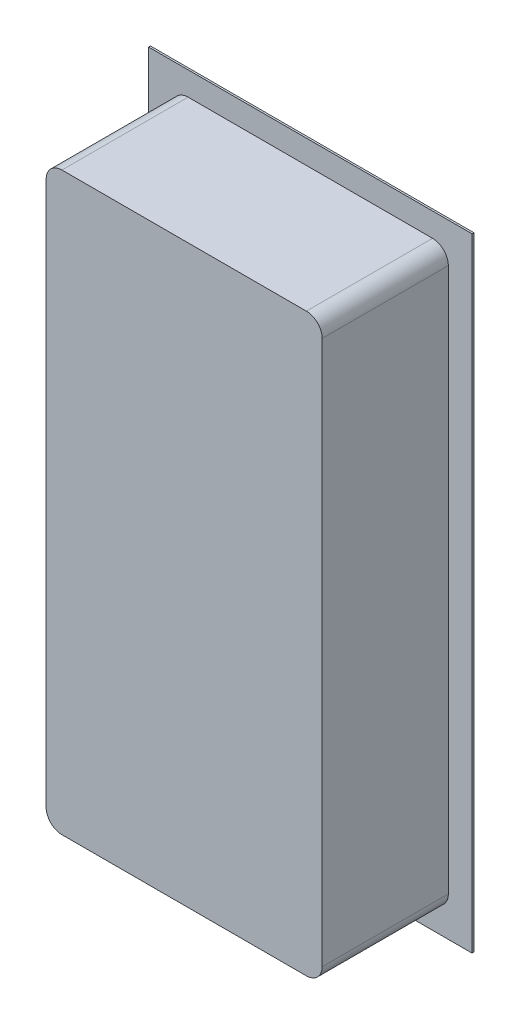
SolidWorks part; units mm, degrees
ref_plane "Front Plane" through (0, 0, 0) normal (0, 0, 1) x (1, 0, 0)
ref_plane "Top Plane" through (0, 0, 0) normal (0, 1, 0) x (1, 0, 0)
ref_plane "Right Plane" through (0, 0, 0) normal (1, 0, 0) x (0, 0, -1)
sketch "Sketch1" plane through (0, 0, 0) normal (0, 0, 1) x (1, 0, 0)
  line L1 (111.125, -231.775) -> (-111.125, -231.775)
  line L2 (111.125, -231.775) -> (111.125, 231.775)
  line L3 (111.125, 231.775) -> (-111.125, 231.775)
  line L4 (-111.125, -231.775) -> (-111.125, 231.775)
  line L5 (111.125, -231.775) -> (-111.125, 231.775) construction
  line L6 (111.125, 231.775) -> (-111.125, -231.775) construction
  point P0 (0, 0)
  dimension "D1" = 222.25
  dimension "D2" = 463.55
extrude "Boss-Extrude1" add sketch "Sketch1" along normal blind 101.6
sketch "Sketch2" plane through (0, 0, 0) normal (0, 0, -1) x (-1, 0, 0)
  line L1 (130.175, -250.825) -> (-130.175, -250.825)
  line L2 (130.175, -250.825) -> (130.175, 250.825)
  line L3 (130.175, 250.825) -> (-130.175, 250.825)
  line L4 (-130.175, -250.825) -> (-130.175, 250.825)
  line L5 (130.175, -250.825) -> (-130.175, 250.825) construction
  line L6 (130.175, 250.825) -> (-130.175, -250.825) construction
  point P0 (0, 0)
  dimension "D1" = 260.35
  dimension "D2" = 501.65
extrude "Boss-Extrude2" add sketch "Sketch2" along normal blind 1.5
fillet "Fillet1" radius 12.7 4 edges at (-111.125, -231.775, 50.8) (111.125, -231.775, 50.8) (-111.125, 231.775, 50.8) (111.125, 231.775, 50.8)
